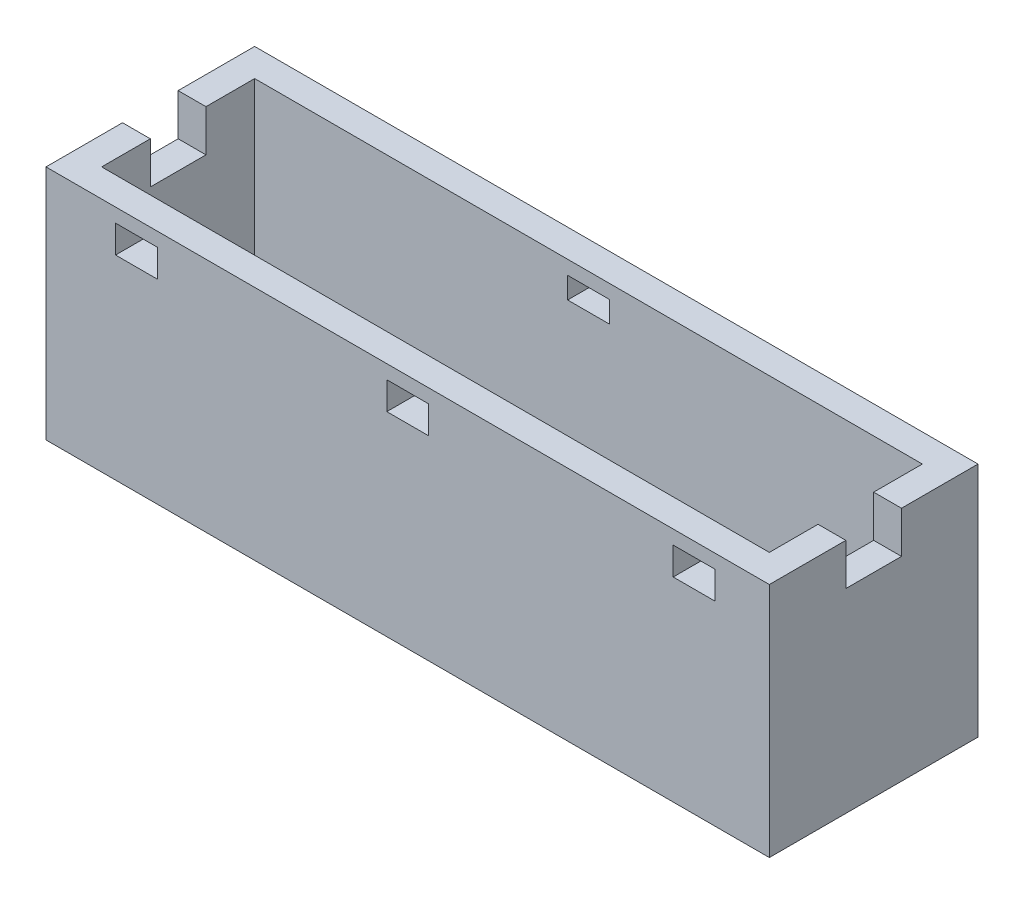
SolidWorks part; units mm, degrees
ref_plane "前基準面" through (0, 0, 0) normal (0, 0, 1) x (1, 0, 0)
ref_plane "上基準面" through (0, 0, 0) normal (0, 1, 0) x (1, 0, 0)
ref_plane "右基準面" through (0, 0, 0) normal (1, 0, 0) x (0, 0, -1)
sketch "草圖1" plane through (0, 0, 0) normal (0, 1, 0) x (1, 0, 0)
  line L1 (-260, 75) -> (260, 75)
  line L2 (-260, 75) -> (-260, -75)
  line L3 (-260, -75) -> (260, -75)
  line L4 (260, 75) -> (260, -75)
  line L5 (-260, 75) -> (260, -75) construction
  line L6 (-260, -75) -> (260, 75) construction
  point P0 (0, 0)
  dimension "D1" = 520
  dimension "D2" = 150
extrude "填料-伸長1" add sketch "草圖1" along normal blind 140
sketch "草圖2" plane through (0, 140, 0) normal (0, 1, 0) x (1, 0, 0)
  line L0 (260, 75) -> (-260, 75) construction
  line L1 (-240, 55) -> (240, 55)
  line L2 (-240, 55) -> (-240, -55)
  line L3 (-240, -55) -> (240, -55)
  line L4 (240, 55) -> (240, -55)
  line L5 (-240, 55) -> (240, -55) construction
  line L6 (-240, -55) -> (240, 55) construction
  line L7 (-260, 75) -> (-260, -75) construction
  point P0 (0, 0)
  dimension "D1" = 20
  dimension "D2" = 20
extrude "除料-伸長1" cut sketch "草圖2" against normal blind 120
ref_plane "平面1" through (0, 0, 80) normal (0, 0, 1) x (1, 0, 0)
sketch "草圖11" plane through (-260, 0, 0) normal (-1, 0, 0) x (0, 0, 1)
  line L0 (-75, 140) -> (75, 140) construction
  line L1 (-20, 140) -> (20, 140)
  line L2 (-20, 140) -> (-20, 110)
  line L3 (-20, 110) -> (20, 110)
  line L4 (20, 140) -> (20, 110)
  line L5 (-75, 140) -> (-75, 0) construction
  dimension "D1" = 40
  dimension "D2" = 30
  dimension "D3" = 55
extrude "除料-伸長3" cut sketch "草圖11" against normal through all
sketch "草圖13" plane through (0, 0, 0) normal (0, -1, 0) x (1, 0, 0)
  line L1 (-260, -75) -> (260, -75)
  line L2 (-260, -75) -> (-260, 75)
  line L3 (-260, 75) -> (260, 75)
  line L4 (260, -75) -> (260, 75)
extrude "填料-伸長6" add sketch "草圖13" along normal blind 30
sketch "草圖18" plane through (0, 0, -75) normal (0, 0, -1) x (-1, 0, 0)
  line L0 (-260, 140) -> (-260, -30) construction
  line L1 (-15, 130) -> (15, 130)
  line L2 (-15, 130) -> (-15, 114.647)
  line L3 (-15, 114.647) -> (15, 114.647)
  line L4 (15, 130) -> (15, 114.647)
  line L5 (-15, 130) -> (15, 114.647) construction
  line L6 (-15, 114.647) -> (15, 130) construction
  line L7 (260, 140) -> (260, -30) construction
  line L8 (-260, 140) -> (260, 140) construction
  point P0 (0, 122.3235)
  dimension "D1" = 245
  dimension "D2" = 245
  dimension "D3" = 10
extrude "除料-伸長8" cut sketch "草圖18" against normal blind 30
sketch "草圖21" plane through (0, 0, 75) normal (0, 0, 1) x (1, 0, 0)
  line L0 (-260, 140) -> (-260, -30) construction
  line L1 (-210, 130) -> (-180, 130)
  line L2 (-210, 130) -> (-210, 110.1244)
  line L3 (-210, 110.1244) -> (-180, 110.1244)
  line L4 (-180, 130) -> (-180, 110.1244)
  line L5 (-210, 130) -> (-180, 110.1244) construction
  line L6 (-210, 110.1244) -> (-180, 130) construction
  line L7 (-260, 140) -> (260, 140) construction
  point P0 (-195, 120.0622)
  dimension "D1" = 50
  dimension "D2" = 10
  dimension "D3" = 30
extrude "除料-伸長9" cut sketch "草圖21" against normal blind 30
sketch "草圖22" plane through (0, 0, 75) normal (0, 0, 1) x (1, 0, 0)
  line L0 (0, -1000) -> (0, 49000) construction
  line L2 (-260, 140) -> (260, 140) construction
  line L3 (-15, 130) -> (15, 130)
  line L4 (-15, 130) -> (-15, 110.12)
  line L5 (-15, 110.12) -> (15, 110.12)
  line L6 (15, 130) -> (15, 110.12)
  line L7 (-15, 130) -> (15, 110.12) construction
  line L8 (-15, 110.12) -> (15, 130) construction
  point P5 (0, 120.06)
  dimension "D1" = 10
  dimension "D2" = 30
  dimension "D3" = 19.88
extrude "除料-伸長10" cut sketch "草圖22" against normal blind 30
sketch "草圖25" plane through (0, 0, 75) normal (0, 0, 1) x (1, 0, 0)
  line L0 (-260, 140) -> (260, 140) construction
  line L1 (190.8911, 130) -> (220.8911, 130)
  line L2 (190.8911, 130) -> (190.8911, 110.12)
  line L3 (190.8911, 110.12) -> (220.8911, 110.12)
  line L4 (220.8911, 130) -> (220.8911, 110.12)
  line L5 (190.8911, 130) -> (220.8911, 110.12) construction
  line L6 (190.8911, 110.12) -> (220.8911, 130) construction
  point P0 (205.8911, 120.06)
  dimension "D1" = 10
  dimension "D2" = 19.88
  dimension "D3" = 30
extrude "除料-伸長12" cut sketch "草圖25" against normal blind 30
